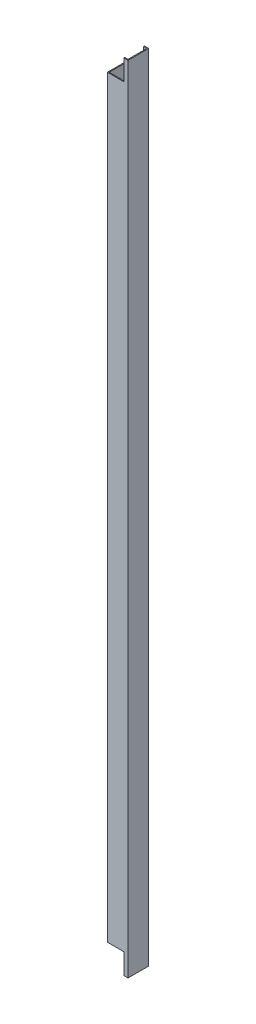
SolidWorks part; units mm, degrees
ref_plane "Front Plane" through (0, 0, 0) normal (0, 0, 1) x (1, 0, 0)
ref_plane "Top Plane" through (0, 0, 0) normal (0, 1, 0) x (1, 0, 0)
ref_plane "Right Plane" through (0, 0, 0) normal (1, 0, 0) x (0, 0, -1)
sketch "Sketch1" plane through (0, 0, 0) normal (0, 1, 0) x (1, 0, 0)
  line L0 (0, 0) -> (0, 50)
  line L1 (0, 50) -> (50, 50)
  line L2 (50, 50) -> (50, 0)
  line L3 (50, 0) -> (0, 0)
  line L4 (2.2, 47.8) -> (47.8, 47.8)
  line L5 (47.8, 47.8) -> (47.8, 2.2)
  line L6 (47.8, 2.2) -> (2.2, 2.2)
  line L7 (2.2, 2.2) -> (2.2, 47.8)
  dimension "D1" = 50
  dimension "D2" = 50
  dimension "D3" = 2.2
extrude "Boss-Extrude1" add sketch "Sketch1" along normal blind 1923
sketch "Sketch2" plane through (0, 0, 0) normal (0, 0, 1) x (1, 0, 0)
  line L0 (0, 0) -> (0, 50)
  line L1 (0, 1923) -> (0, 0) construction
  line L2 (0, 50) -> (40, 50)
  line L3 (40, 50) -> (40, 0)
  line L5 (40, 0) -> (0, 0)
  line L6 (0, 1923) -> (40, 1923)
  line L7 (0, 1923) -> (50, 1923) construction
  line L8 (40, 1923) -> (40, 1873)
  line L9 (40, 1873) -> (0, 1873)
  line L10 (0, 1873) -> (0, 1923)
  dimension "D1" = 50
  dimension "D2" = 40
  dimension "D3" = 50
  dimension "D4" = 40
extrude "Cut-Extrude2" cut sketch "Sketch2" against normal blind 50
equation "\"SquareTube_length\"=1923.0"
equation "\"D1@Boss-Extrude1\"=\"SquareTube_length\""
equation "\"SquareTube_inBack1_cutDepth50_R\"=50"
equation "\"D1@Sketch2\" = \"SquareTube_inBack3_cutDepth50_R\""
equation "\"SquareTube_inBack1_cutDepth50_L\"=50"
equation "\"D3@Sketch2\" = \"SquareTube_inBack3_cutDepth50_L\""
equation "\"CarBeamWidth\"=700.0"
equation "\"MetalSheet_3mm_length\"=5030.0"
equation "\"MetalSheet_3mm_width\"=1923.0"
equation "\"MetalSheet_3mm_FloorCut_L_length\"=1764.0"
equation "\"MetalSheet_3mm_FloorCut_L_disdance\"=1665.0"
equation "\"MetalSheet_3mm_FloorCut_R_length\"=1764.0"
equation "\"MetalSheet_3mm_FloorCut_R_disdance\"=1665.0"
equation "\"indoorHeight\"=1940.0"
equation "\"x\"=66.0"
equation "\"da\"=62.0"
equation "\"SquareTube_wheel_length\"= 750"
equation "\"channelSteel_length\"=5030.0"
equation "\"SquareTube_inFront1_cutDepth50_R\"=0.5"
equation "\"SquareTube_inFront1_cutDepth50_L\"=0.5"
equation "\"SquareTube_inFront2_cutDepth50_R\"=0.5"
equation "\"SquareTube_inFront2_cutDepth50_L\"=0.5"
equation "\"SquareTube_inFront3_cutDepth50_R\"=0.5"
equation "\"SquareTube_inFront3_cutDepth50_L\"=0.5"
equation "\"SquareTube_inFront4_cutDepth50_R\"=0.5"
equation "\"SquareTube_inFront4_cutDepth50_L\"=0.5"
equation "\"SquareTube_inFront5_cutDepth50_R\"=50"
equation "\"SquareTube_inFront5_cutDepth50_L\"=50"
equation "\"SquareTube_inFront6_cutDepth50_R\"=50"
equation "\"SquareTube_inFront6_cutDepth50_L\"=50"
equation "\"SquareTube_inFront7_cutDepth50_R\"=50"
equation "\"SquareTube_inFront7_cutDepth50_L\"=50"
equation "\"SquareTube_inFront8_cutDepth50_R\"=50"
equation "\"SquareTube_inFront8_cutDepth50_L\"=50"
equation "\"SquareTube_inFront9_cutDepth50_R\"=50"
equation "\"SquareTube_inFront9_cutDepth50_L\"=50"
equation "\"SquareTube_inFront10_cutDepth50_R\"=50"
equation "\"SquareTube_inFront10_cutDepth50_L\"=50"
equation "\"SquareTube_inBack2_cutDepth50_R\"=50"
equation "\"SquareTube_inBack2_cutDepth50_L\"=50"
equation "\"SquareTube_inBack3_cutDepth50_R\"=50"
equation "\"SquareTube_inBack3_cutDepth50_L\"=50"
equation "\"SquareTube_inBack4_cutDepth50_R\"=50"
equation "\"SquareTube_inBack4_cutDepth50_L\"=50"
equation "\"SquareTube_inBack5_cutDepth50_R\"=50"
equation "\"SquareTube_inBack5_cutDepth50_L\"=50"
equation "\"SquareTube_inBack6_cutDepth50_R\"=0.5"
equation "\"SquareTube_inBack6_cutDepth50_L\"=0.5"
equation "\"SquareTube_inFront11_cutDepth50_R\"=50"
equation "\"SquareTube_inFront11_cutDepth50_L\"=50"
equation "\"SquareTube_inFront12_cutDepth50_R\"=50"
equation "\"SquareTube_inFront12_cutDepth50_L\"=50"
equation "\"SquareTube_inFront13_cutDepth50_R\"=50"
equation "\"SquareTube_inFront13_cutDepth50_L\"=50"
equation "\"SquareTube_inFront14_cutDepth50_R\"=50"
equation "\"SquareTube_inFront14_cutDepth50_L\"=50"
equation "\"SquareTube_inBack7_cutDepth50_R\"=0.5"
equation "\"SquareTube_inBack7_cutDepth50_L\"=0.5"
equation "\"SquareTube_inBack8_cutDepth50_R\"=0.5"
equation "\"SquareTube_inBack8_cutDepth50_L\"=0.5"
